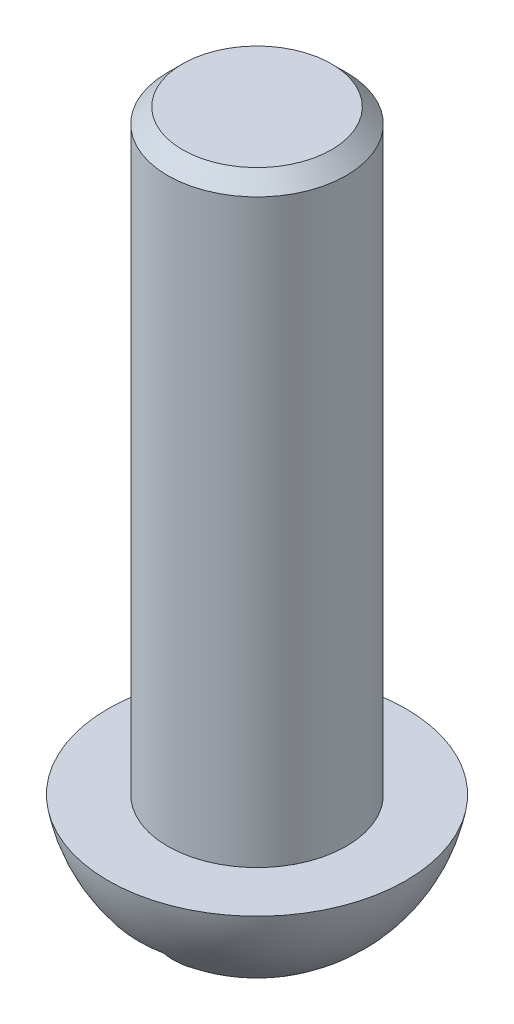
SolidWorks part; units mm, degrees
material "Plain Carbon Steel"
ref_plane "Спереди" through (0, 0, 0) normal (0, 0, 1) x (1, 0, 0)
ref_plane "Сверху" through (0, 0, 0) normal (0, 1, 0) x (1, 0, 0)
ref_plane "Справа" through (0, 0, 0) normal (1, 0, 0) x (0, 0, -1)
sketch "Sketch1" plane through (0, 0, 0) normal (0, 1, 0) x (1, 0, 0)
  circle A0 centre (0, 0) radius 3
  dimension "D1" = 6
extrude "Boss-Extrude1" add sketch "Sketch1" along normal blind 20
chamfer "Chamfer1" distance 0.5 angle 45 1 edges at (0, 20, 3)
sketch "Sketch2" plane through (0, 0, 0) normal (0, 0, 1) x (1, 0, 0)
  line L0 (0, 0) -> (-5, 0)
  line L1 (0, -4.2) -> (0, 0) construction
  line L2 (0, 0) -> (0, -4.2)
  arc A0 (-5, 0) -> (0, -4.2) centre (0.02, 0.9) ccw
  dimension "D3" = 5.1
  dimension "D1" = 5
  dimension "D2" = 4.2
revolve "Revolve1" add sketch "Sketch2" angle 360 about L1
sketch "Sketch3" plane through (0, 0, 0) normal (0, 0, 1) x (1, 0, 0)
  line L0 (-0.7603, -2.29) -> (0, -2.29)
  line L1 (0, -2.29) -> (0.7603, -2.29)
  line L2 (0.7603, -2.29) -> (0.7603, -6.2281)
  line L3 (0.7603, -6.2281) -> (-0.7603, -6.2281)
  line L4 (-0.7603, -6.2281) -> (-0.7603, -2.29)
  dimension "D1" = 2.29
extrude "Cut-Extrude1" cut sketch "Sketch3" against normal through all and the other way through all
